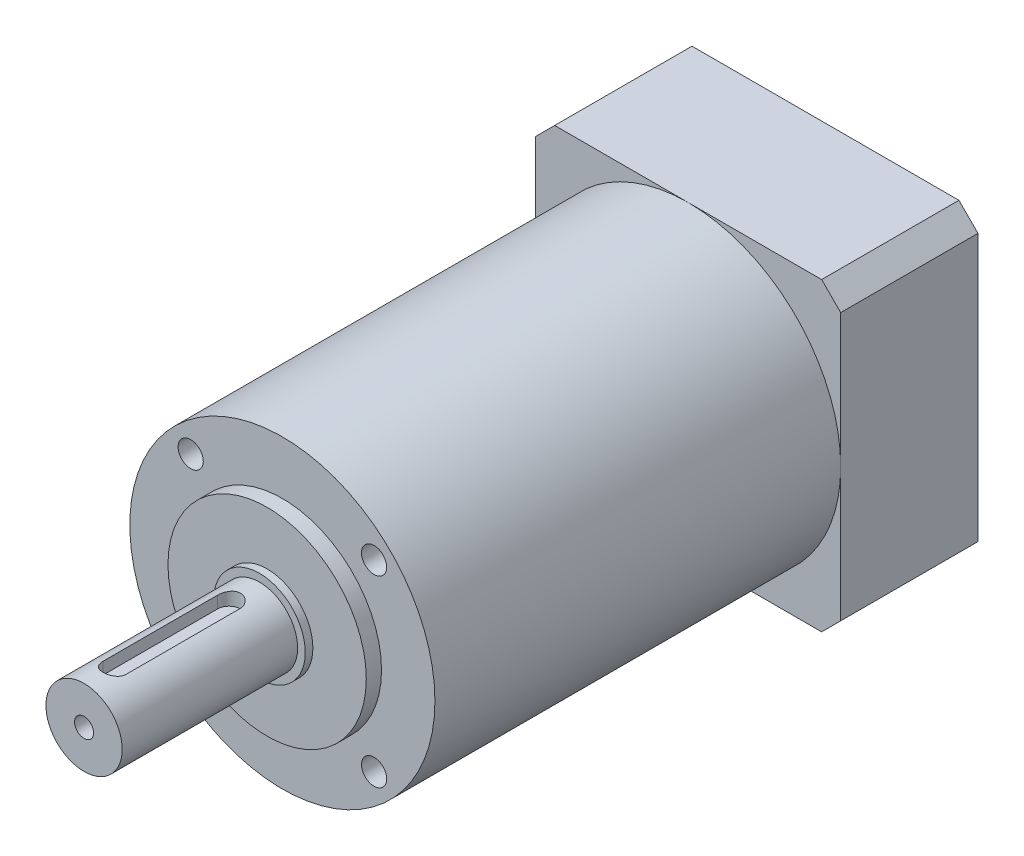
SolidWorks part; units mm, degrees
ref_plane "Front" through (0, 0, 0) normal (0, 0, 1) x (1, 0, 0)
ref_plane "Top" through (0, 0, 0) normal (0, 1, 0) x (1, 0, 0)
ref_plane "Right" through (0, 0, 0) normal (1, 0, 0) x (0, 0, -1)
sketch "Эскиз1" plane through (0, 0, 0) normal (0, 0, 1) x (1, 0, 0)
  line L1 (0, 0) -> (40, 0)
  line L2 (0, 0) -> (0, 40)
  line L3 (0, 40) -> (40, 40)
  line L4 (40, 0) -> (40, 40)
  dimension "D1" = 40
  dimension "D2" = 40
extrude "Бобышка-Вытянуть1" add sketch "Эскиз1" along normal blind 18
sketch "Эскиз2" plane through (0, 0, 18) normal (0, 0, 1) x (1, 0, 0)
  line L1 (0, 0) -> (40, 0) construction
  line L2 (40, 0) -> (40, 40) construction
  circle A0 centre (20, 20) radius 20
  dimension "D1" = 40
extrude "Бобышка-Вытянуть2" add sketch "Эскиз2" along normal blind 53.2
sketch "Эскиз3" plane through (0, 0, 71.2) normal (0, 0, 1) x (1, 0, 0)
  circle A0 centre (20, 20) radius 13
  arc A1 (40, 20) -> (20, 40) centre (20, 20) ccw construction
  dimension "D1" = 26
extrude "Бобышка-Вытянуть3" add sketch "Эскиз3" along normal blind 2
sketch "Эскиз4" plane through (0, 0, 73.2) normal (0, 0, 1) x (1, 0, 0)
  circle A0 centre (20, 20) radius 6
  circle A1 centre (20, 20) radius 13 construction
  dimension "D1" = 12
extrude "Бобышка-Вытянуть4" add sketch "Эскиз4" along normal blind 1
sketch "Эскиз5" plane through (0, 0, 74.2) normal (0, 0, 1) x (1, 0, 0)
  circle A0 centre (20, 20) radius 5
  circle A1 centre (20, 20) radius 6 construction
  dimension "D1" = 10
extrude "Бобышка-Вытянуть5" add sketch "Эскиз5" along normal blind 23 contours A0
ref_plane "Плоскость3" through (0, 25, 0) normal (0, -1, 0) x (-1, 0, 0)
sketch "Эскиз9" plane through (0, 25, 0) normal (0, -1, 0) x (-1, 0, 0)
  line L0 (-20, -93.2) -> (-20, -78.2) construction
  line L1 (-21.5, -93.2) -> (-21.5, -78.2)
  line L2 (-18.5, -93.2) -> (-18.5, -78.2)
  line L3 (-25, -97.2) -> (-15, -97.2) construction
  arc A0 (-21.5, -93.2) -> (-18.5, -93.2) centre (-20, -93.2) ccw
  arc A1 (-18.5, -78.2) -> (-21.5, -78.2) centre (-20, -78.2) ccw
  point P2 (-20, -85.7)
  dimension "D2" = 1.5
  dimension "D1" = 15
  dimension "D3" = 4
  dimension "D4" = 20
extrude "Вырез-Вытянуть1" cut sketch "Эскиз9" along normal blind 1.8
hole_wizard "Отверстие обработанное метчиком M31" positions "Эскиз11" profile "Эскиз10" tap size "M3" standard "DIN"
sketch "Эскиз11" plane through (0, 0, 97.2) normal (0, 0, 1) x (1, 0, 0)
  circle A0 centre (20, 20) radius 6 construction
  point P0 (20, 20)
sketch "Эскиз10" plane through (20, 20, 97.2) normal (1, 0, 0) x (0, -1, 0)
  line L0 (0, 0) -> (0, 15.7511)
  line L1 (0, 15.7511) -> (1.25, 15)
  line L2 (1.25, 15) -> (1.25, 0)
  line L5 (1.25, 0) -> (0, 0)
  line L10 (0, 15.7511) -> (-1.25, 15) construction
  line L11 (0, -6.35) -> (0, 107.95) construction
  dimension "Диаметр сверла" = 2.5
  dimension "Глубина сверла" = 15
  dimension "Угол заточки сверла" = 118
cosmetic thread "Отверстие резьбы1" parameters "D1"=10, "D2"=3
sketch "Эскиз12" plane through (0, 0, 71.2) normal (0, 0, 1) x (1, 0, 0)
  line L0 (7.9792, 32.0208) -> (20, 20)
  line L1 (20, 20) -> (3, 20)
  circle A0 centre (20, 20) radius 17
  point P3 (7.9792, 32.0208)
  dimension "D1" = 34
  dimension "D2" = 45
hole_wizard "Отверстие обработанное метчиком M41" positions "Эскиз13" profile "Эскиз14" tap size "M4" standard "DIN"
sketch "Эскиз13" plane through (0, 0, 71.2) normal (0, 0, 1) x (1, 0, 0)
  point P0 (7.9792, 32.0208)
sketch "Эскиз14" plane through (7.9792, 32.0208, 71.2) normal (1, 0, 0) x (0, -1, 0)
  line L0 (0, 0) -> (0, 7.9914)
  line L1 (0, 7.9914) -> (1.65, 7)
  line L2 (1.65, 7) -> (1.65, 0)
  line L5 (1.65, 0) -> (0, 0)
  line L10 (0, 7.9914) -> (-1.65, 7) construction
  line L11 (0, -6.35) -> (0, 107.95) construction
  dimension "Диаметр сверла" = 3.3
  dimension "Глубина сверла" = 7
  dimension "Угол заточки сверла" = 118
cosmetic thread "Отверстие резьбы2" parameters "D1"=7, "D2"=4
pattern_circular "Круговой массив1" count 4 over 360 about axis through (20, 20, 0) along (0, 0, 1) of "Отверстие обработанное метчиком M41"
cosmetic thread "Отверстие резьбы3" parameters "D1"=7, "D2"=4
cosmetic thread "Отверстие резьбы4" parameters "D1"=7, "D2"=4
cosmetic thread "Отверстие резьбы5" parameters "D1"=7, "D2"=4
chamfer "Фаска1" distance 2.5 angle 45 4 edges at (0, 0, 9) (40, 0, 9) (40, 40, 9) (0, 40, 9)
sketch "Эскиз15" plane through (0, 0, 0) normal (0, 0, -1) x (-1, 0, 0)
  circle A0 centre (-20, 20) radius 16.5
  dimension "D3" = 33
  dimension "D1" = 20
  dimension "D2" = 20
extrude "Вырез-Вытянуть2" cut sketch "Эскиз15" against normal blind 18
sketch "Эскиз16" plane through (0, 0, 18) normal (0, 0, -1) x (-1, 0, 0)
  line L3 (-21, 14.5917) -> (-21, 11.0557)
  line L5 (-19, 14.5917) -> (-19, 11.0557)
  arc A0 (-19, 14.5917) -> (-21, 14.5917) centre (-20, 20) ccw
  arc A1 (-19, 11.0557) -> (-21, 11.0557) centre (-20, 20) ccw
  dimension "D1" = 11
  dimension "D2" = 18
  dimension "D3" = 20
  dimension "D4" = 20
  dimension "D5" = 2
  dimension "D6" = 19
extrude "Бобышка-Вытянуть6" add sketch "Эскиз16" along normal blind 15
fillet "Скругление1" radius 0.5 2 edges at (20, 25.5, 3) (20, 29, 3)
sketch "Эскиз17" plane through (0, 0, 18) normal (0, 0, -1) x (-1, 0, 0)
  circle A0 centre (-20, 20) radius 9
  circle A1 centre (-20, 20) radius 13.5
  dimension "D1" = 27
  dimension "D2" = 18
extrude "Бобышка-Вытянуть7" add sketch "Эскиз17" along normal blind 16
fillet "Скругление2" radius 0.5 1 edges at (11, 20, 2)
sketch "Эскиз18" plane through (0, 0, 0) normal (0, 0, -1) x (-1, 0, 0)
  line L0 (-36.3, 36.3) -> (-20, 20)
  line L2 (-2.5, 0) -> (0, 2.5) construction
  line L3 (-1.25, 1.25) -> (-38.75, 1.25)
  line L4 (-40, 2.5) -> (-37.5, 0) construction
  line L5 (-20, 20) -> (-36.3, 36.3)
  line L7 (-36.3, 36.3) -> (-32.6, 40)
  line L8 (-37.5, 40) -> (-2.5, 40) construction
  line L9 (-32.6, 40) -> (-36.3, 36.3)
  point P0 (-36.3, 36.3)
  point P1 (-20, 20)
  dimension "D1" = 16.3
  dimension "D2" = 16.3
hole_wizard "Отверстие обработанное метчиком M43" positions "Эскиз21" profile "Эскиз22" tap size "M4" standard "DIN"
sketch "Эскиз21" plane through (0, 0, 0) normal (0, 0, -1) x (-1, 0, 0)
  point P0 (-36.3, 36.3)
sketch "Эскиз22" plane through (36.3, 36.3, 0) normal (1, 0, 0) x (0, 1, 0)
  line L0 (0, 0) -> (0, 12.4914)
  line L1 (0, 12.4914) -> (1.65, 11.5)
  line L2 (1.65, 11.5) -> (1.65, 0)
  line L5 (1.65, 0) -> (0, 0)
  line L10 (0, 12.4914) -> (-1.65, 11.5) construction
  line L11 (0, -6.35) -> (0, 107.95) construction
  dimension "Диаметр сверла" = 3.3
  dimension "Глубина сверла" = 11.5
  dimension "Угол заточки сверла" = 118
cosmetic thread "Отверстие резьбы7" parameters "D1"=8, "D2"=4
pattern_circular "Круговой массив2" count 4 over 360 about axis through (20, 20, 0) along (0, 0, 1) of "Отверстие обработанное метчиком M43"
cosmetic thread "Отверстие резьбы8" parameters "D1"=8, "D2"=4
cosmetic thread "Отверстие резьбы9" parameters "D1"=8, "D2"=4
cosmetic thread "Отверстие резьбы10" parameters "D1"=8, "D2"=4
